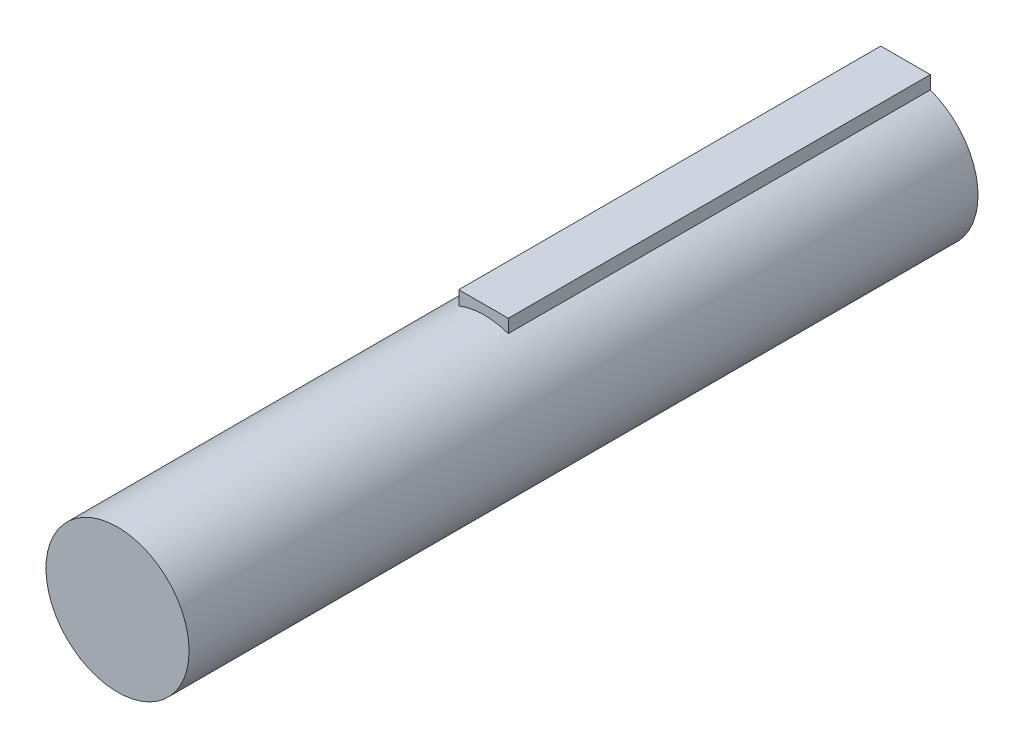
SolidWorks part; units mm, degrees
ref_plane "前视基准面" through (0, 0, 0) normal (0, 0, 1) x (1, 0, 0)
ref_plane "上视基准面" through (0, 0, 0) normal (0, 1, 0) x (1, 0, 0)
ref_plane "右视基准面" through (0, 0, 0) normal (1, 0, 0) x (0, 0, -1)
sketch "草图1" plane through (0, 0, 0) normal (0, 0, 1) x (1, 0, 0)
  line L2 (-1.4, 3.6401) -> (-1.4, 4.4)
  line L3 (-1.4, 4.4) -> (1.3, 4.4)
  line L4 (1.3, 3.677) -> (1.3, 4.4)
  line L5 (-1.475, 3.3327) -> (1.3, 4.4) construction
  line L6 (-1.4, 4.4) -> (1.2573, 3.451) construction
  arc A0 (-1.4, 3.6401) -> (1.3, 3.677) centre (0, 0) ccw
  point P3 (0, 3.9)
  dimension "D1" = 7.8
  dimension "D2" = 2.7
  dimension "D3" = 0.95
extrude "凸台-拉伸1" add sketch "草图1" along normal blind 23
sketch "草图2" plane through (0, 0, 23) normal (0, 0, 1) x (1, 0, 0)
  circle A1 centre (0, 0) radius 3.9
extrude "凸台-拉伸2" add sketch "草图2" along normal blind 20
